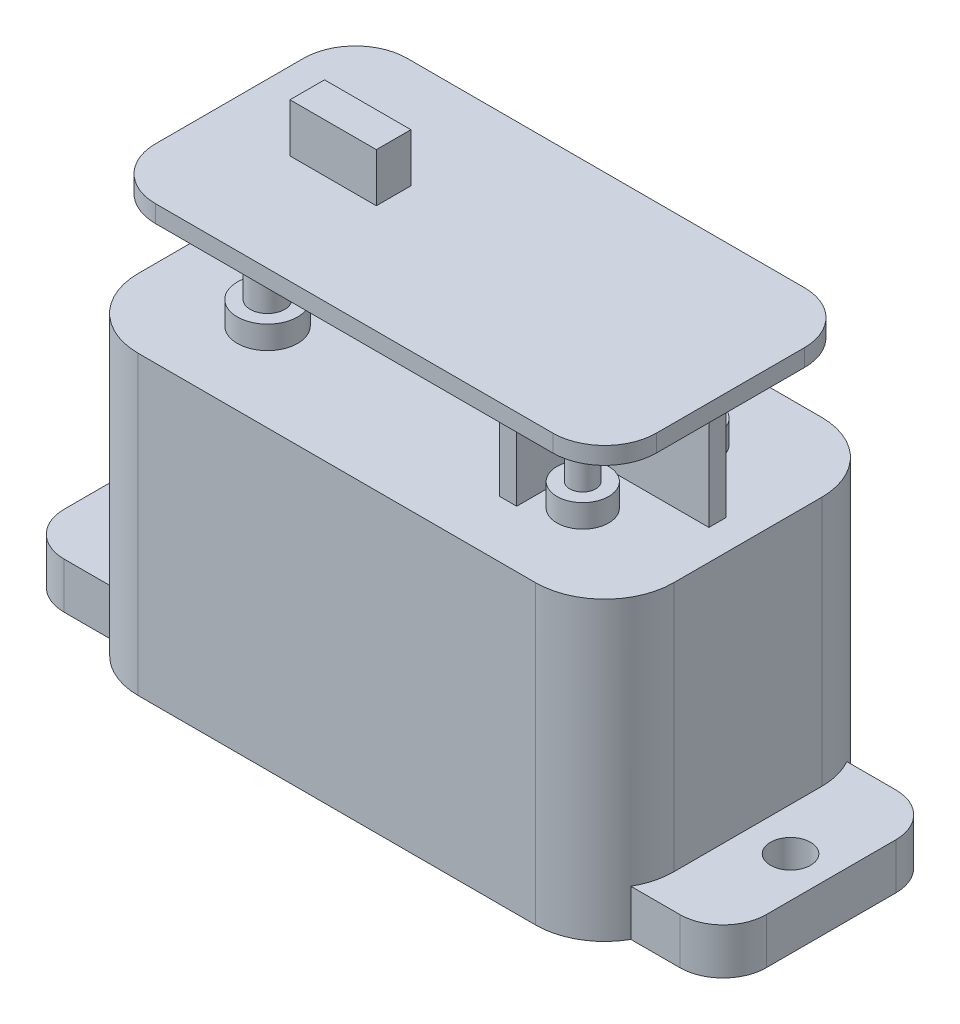
SolidWorks part; units mm, degrees
ref_plane "Front Plane" through (0, 0, 0) normal (0, 0, 1) x (1, 0, 0)
ref_plane "Top Plane" through (0, 0, 0) normal (0, 1, 0) x (1, 0, 0)
ref_plane "Right Plane" through (0, 0, 0) normal (1, 0, 0) x (0, 0, -1)
sketch "Sketch1" plane through (0, 0, 0) normal (0, 1, 0) x (1, 0, 0)
  line L0 (-35.95, 0) -> (35.95, 0) construction
  line L1 (35.64, -12.5) -> (-35.64, -12.5)
  line L2 (40.64, -7.5) -> (40.64, 7.5)
  line L3 (35.64, 12.5) -> (-35.64, 12.5)
  line L4 (-40.64, -7.5) -> (-40.64, 7.5)
  line L5 (40.64, -12.5) -> (-40.64, 12.5) construction
  line L6 (40.64, 12.5) -> (-40.64, -12.5) construction
  arc A0 (40.64, 7.5) -> (35.64, 12.5) centre (35.64, 7.5) ccw
  arc A1 (35.64, -12.5) -> (40.64, -7.5) centre (35.64, -7.5) ccw
  arc A2 (-35.64, -12.5) -> (-40.64, -7.5) centre (-35.64, -7.5) cw
  arc A3 (-35.64, 12.5) -> (-40.64, 7.5) centre (-35.64, 7.5) ccw
  circle A4 centre (-35.95, 0) radius 2.32
  circle A5 centre (35.95, 0) radius 2.32
  point P0 (0, 0)
  point P22 (32.667, -3.4925)
  point P23 (0, 0)
  dimension "D3" = 5
  dimension "D4" = 4.64
  dimension "D1" = 25
  dimension "D2" = 81.28
  dimension "D5" = 71.9
extrude "Boss-Extrude1" add sketch "Sketch1" along normal blind 5.33
sketch "Sketch2" plane through (0, 0, 0) normal (0, -1, 0) x (1, 0, 0)
  line L1 (23, 16.57) -> (-23, 16.57)
  line L2 (31, 8.57) -> (31, -8.57)
  line L3 (23, -16.57) -> (-23, -16.57)
  line L4 (-31, 8.57) -> (-31, -8.57)
  line L5 (31, 16.57) -> (-31, -16.57) construction
  line L6 (31, -16.57) -> (-31, 16.57) construction
  arc A0 (-23, -16.57) -> (-31, -8.57) centre (-23, -8.57) cw
  arc A1 (31, -8.57) -> (23, -16.57) centre (23, -8.57) cw
  arc A2 (23, 16.57) -> (31, 8.57) centre (23, 8.57) cw
  arc A3 (-23, 16.57) -> (-31, 8.57) centre (-23, 8.57) ccw
  point P0 (0, 0)
  dimension "D3" = 8
  dimension "D1" = 33.14
  dimension "D2" = 62
extrude "Boss-Extrude2" add sketch "Sketch2" against normal blind 34.32
sketch "Sketch3" plane through (0, 34.32, 0) normal (0, 1, 0) x (1, 0, 0)
  line L1 (18.25, -6.35) -> (-18.25, -6.35) construction
  line L2 (18.25, -6.35) -> (18.25, 6.35) construction
  line L3 (18.25, 6.35) -> (-18.25, 6.35) construction
  line L4 (-18.25, -6.35) -> (-18.25, 6.35) construction
  line L5 (18.25, -6.35) -> (-18.25, 6.35) construction
  line L6 (18.25, 6.35) -> (-18.25, -6.35) construction
  circle A0 centre (-18.25, 6.35) radius 3.5
  circle A1 centre (-18.25, -6.35) radius 3.5
  circle A2 centre (18.25, -6.35) radius 3
  circle A3 centre (18.25, 6.35) radius 3
  point P0 (0, 0)
  dimension "D1" = 7
  dimension "D2" = 6
  dimension "D3" = 12.7
  dimension "D4" = 36.5
extrude "Boss-Extrude3" add sketch "Sketch3" along normal offset from surface (2.66 mm away) 36.98 up to face at (0, 0, 0)
sketch "Sketch4" plane through (0, 36.98, 0) normal (0, 1, 0) x (1, 0, 0)
  circle A0 centre (-18.25, 6.35) radius 2
  circle A1 centre (-18.25, -6.35) radius 2
  circle A2 centre (18.25, 6.35) radius 1.5
  circle A3 centre (18.25, -6.35) radius 1.5
  dimension "D1" = 4
  dimension "D2" = 3
extrude "Boss-Extrude4" add sketch "Sketch4" along normal blind 8
sketch "Sketch5" plane through (0, 34.32, 0) normal (0, 1, 0) x (1, 0, 0)
  line L0 (12.25, 1) -> (-27.5, 1)
  line L1 (27.5, -1) -> (14.25, -1)
  line L2 (27.5, -1) -> (27.5, 1)
  line L3 (27.5, 1) -> (14.25, 1)
  line L4 (-27.5, -1) -> (-27.5, 1)
  line L5 (27.5, -1) -> (-27.5, 1) construction
  line L6 (27.5, 1) -> (-27.5, -1) construction
  line L7 (12.25, -10) -> (14.25, -10)
  line L8 (12.25, -10) -> (12.25, -1)
  line L9 (12.25, 10) -> (14.25, 10)
  line L10 (14.25, -10) -> (14.25, -1)
  line L11 (12.25, -10) -> (14.25, 10) construction
  line L12 (12.25, 10) -> (14.25, -10) construction
  line L13 (12.25, 1) -> (12.25, 10)
  line L14 (12.25, -1) -> (-27.5, -1)
  line L15 (14.25, 1) -> (14.25, 10)
  circle A0 centre (18.25, 6.35) radius 1.5 construction
  point P0 (0, 0)
  point P5 (13.25, 0)
  point P13 (0, 0)
  dimension "D1" = 2
  dimension "D2" = 55
  dimension "D3" = 20
  dimension "D4" = 2
  dimension "D5" = 5
extrude "Boss-Extrude5" add sketch "Sketch5" along normal blind 12
sketch "Sketch6" plane through (0, 46.32, 0) normal (0, 1, 0) x (1, 0, 0)
  line L8 (-29, 8.57) -> (-29, -8.57)
  line L9 (-23, -14.57) -> (23, -14.57)
  line L10 (29, -8.57) -> (29, 8.57)
  line L11 (23, 14.57) -> (-23, 14.57)
  line L12 (-29, 8.57) -> (-29, -8.57)
  line L13 (-23, -14.57) -> (23, -14.57)
  line L14 (29, -8.57) -> (29, 8.57)
  line L15 (23, 14.57) -> (-23, 14.57)
  arc A8 (-23, 14.57) -> (-29, 8.57) centre (-23, 8.57) ccw
  arc A9 (-29, -8.57) -> (-23, -14.57) centre (-23, -8.57) ccw
  arc A10 (23, -14.57) -> (29, -8.57) centre (23, -8.57) ccw
  arc A11 (29, 8.57) -> (23, 14.57) centre (23, 8.57) ccw
  arc A12 (-23, 14.57) -> (-29, 8.57) centre (-23, 8.57) ccw
  arc A13 (-29, -8.57) -> (-23, -14.57) centre (-23, -8.57) ccw
  arc A14 (23, -14.57) -> (29, -8.57) centre (23, -8.57) ccw
  arc A15 (29, 8.57) -> (23, 14.57) centre (23, 8.57) ccw
  dimension "D1" = 2
extrude "Boss-Extrude6" add sketch "Sketch6" along normal blind 2
sketch "Sketch7" plane through (0, 48.32, 0) normal (0, 1, 0) x (1, 0, 0)
  line L1 (-20, -2) -> (-10, -2)
  line L2 (-20, -2) -> (-20, 2)
  line L3 (-20, 2) -> (-10, 2)
  line L4 (-10, -2) -> (-10, 2)
  line L5 (-20, -2) -> (-10, 2) construction
  line L6 (-20, 2) -> (-10, -2) construction
  point P0 (-15, 0)
  point P5 (0, 0)
  dimension "D1" = 4
  dimension "D2" = 10
  dimension "D3" = 15
extrude "Boss-Extrude7" add sketch "Sketch7" along normal offset from surface (5.63 mm away) 53.95 up to face at (0, 0, 0)
